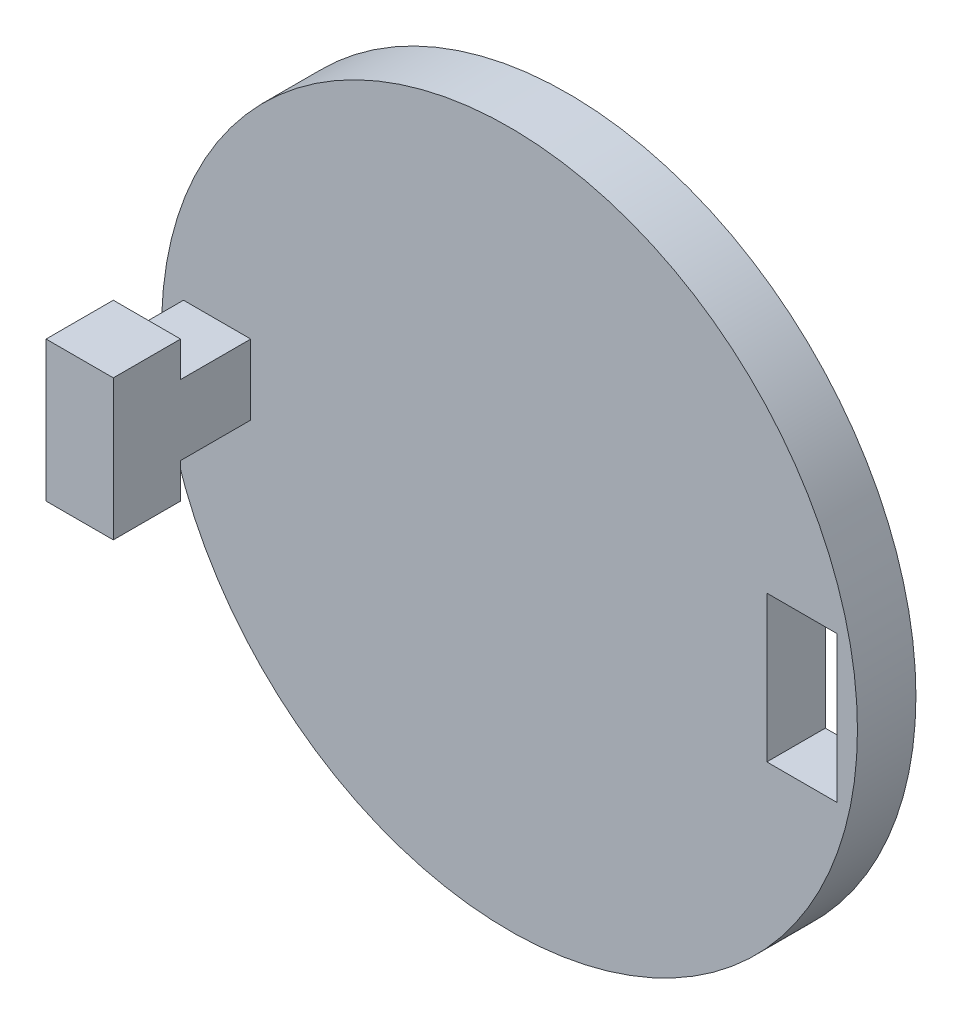
SolidWorks part; units mm, degrees
material "ABS PC"
ref_plane "Front Plane" through (0, 0, 0) normal (0, 0, 1) x (1, 0, 0)
ref_plane "Top Plane" through (0, 0, 0) normal (0, 1, 0) x (1, 0, 0)
ref_plane "Right Plane" through (0, 0, 0) normal (1, 0, 0) x (0, 0, -1)
sketch "Sketch1" plane through (0, 0, 0) normal (0, 0, 1) x (1, 0, 0)
  line L0 (0, 0) -> (0, 6.3935) construction
  line L1 (0, 6.3935) -> (0, 0) construction
  line L2 (0, 0) -> (10, 0) construction
  line L4 (8.8, 2.5) -> (11.2, 2.5)
  line L5 (8.8, 2.5) -> (8.8, -2.5)
  line L6 (8.8, -2.5) -> (11.2, -2.5)
  line L7 (11.2, 2.5) -> (11.2, -2.5)
  line L8 (8.8, 2.5) -> (11.2, -2.5) construction
  line L9 (8.8, -2.5) -> (11.2, 2.5) construction
  circle A0 centre (0, 0) radius 11.9
  dimension "D1" = 10
  dimension "D4" = 23.8
  dimension "D2" = 5
  dimension "D3" = 2.4
extrude "Boss-Extrude2" add sketch "Sketch1" along normal blind 2
sketch "Sketch2" plane through (0, 0, 2) normal (0, 0, 1) x (1, 0, 0)
  line L0 (0, 0) -> (-10, 0) construction
  line L1 (-10, 0) -> (-10, -1.2) construction
  line L7 (-11.15, -2.4) -> (-8.85, 0) construction
  line L8 (-11.15, 0) -> (-8.85, -2.4) construction
  line L9 (-11.15, 1.2) -> (-8.85, 1.2)
  line L10 (-11.15, 1.2) -> (-11.15, -1.2)
  line L11 (-11.15, -1.2) -> (-8.85, -1.2)
  line L12 (-8.85, 1.2) -> (-8.85, -1.2)
  line L13 (-11.15, 1.2) -> (-8.85, -1.2) construction
  line L14 (-11.15, -1.2) -> (-8.85, 1.2) construction
  dimension "D1" = 10
  dimension "D2" = 1.2
  dimension "D3" = 2.3
  dimension "D4" = 2.3
  dimension "D5" = 2.4
extrude "Boss-Extrude3" add sketch "Sketch2" along normal blind 4.7
sketch "Sketch4" plane through (0, 1.2, 0) normal (0, 1, 0) x (1, 0, 0)
  line L0 (-11.15, -6.7) -> (-11.15, -2) construction
  line L1 (-8.85, -6.7) -> (-11.15, -6.7)
  line L2 (-8.85, -6.7) -> (-8.85, -4.4)
  line L3 (-8.85, -4.4) -> (-11.15, -4.4)
  line L4 (-11.15, -6.7) -> (-11.15, -4.4)
  dimension "D1" = 2.3
extrude "Boss-Extrude5" add sketch "Sketch4" along normal blind 1.2
sketch "Sketch5" plane through (0, -1.2, 0) normal (0, -1, 0) x (1, 0, 0)
  line L0 (-8.85, 6.7) -> (-8.85, 2) construction
  line L1 (-11.15, 6.7) -> (-8.85, 6.7)
  line L2 (-11.15, 6.7) -> (-11.15, 4.4)
  line L3 (-11.15, 4.4) -> (-8.85, 4.4)
  line L4 (-8.85, 6.7) -> (-8.85, 4.4)
  dimension "D1" = 2.3
extrude "Boss-Extrude6" add sketch "Sketch5" along normal blind 1.2
